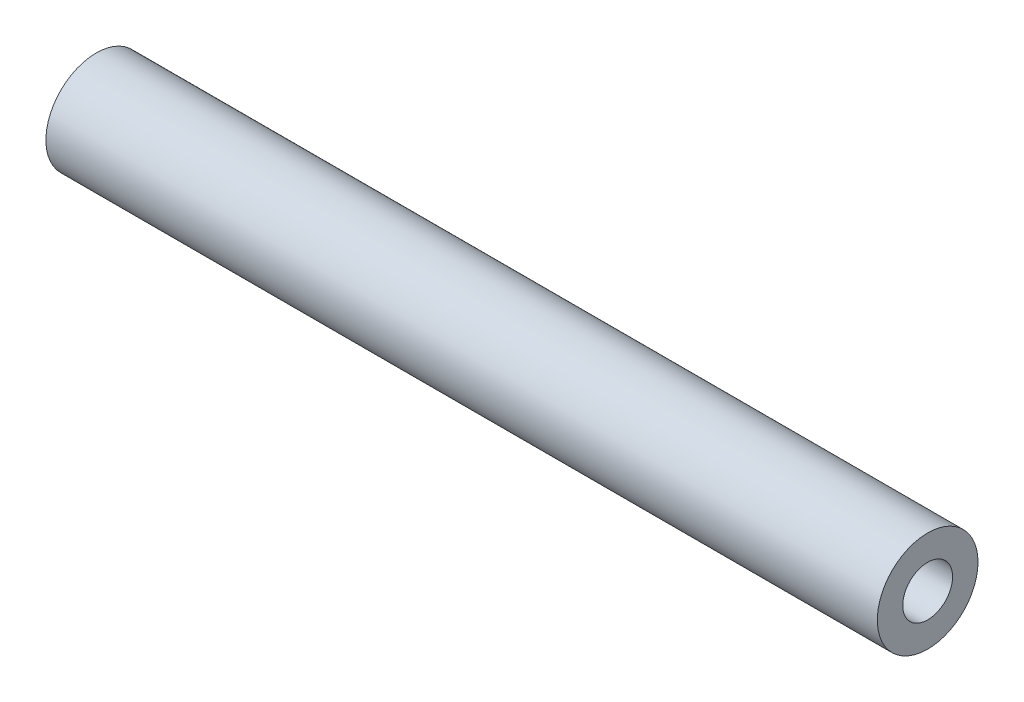
SolidWorks part; units mm, degrees
material "Natural Rubber"
ref_plane "Front Plane" through (0, 0, 0) normal (0, 0, 1) x (1, 0, 0)
ref_plane "Top Plane" through (0, 0, 0) normal (0, 1, 0) x (1, 0, 0)
ref_plane "Right Plane" through (0, 0, 0) normal (1, 0, 0) x (0, 0, -1)
sketch "Sketch2" plane through (0, 0, 0) normal (1, 0, 0) x (0, 0, -1)
  circle A0 centre (-3.3975, -0.6473) radius 15
  circle A1 centre (-3.3975, -0.6473) radius 30.275
  dimension "Inner_port_radius" = 30
  dimension "outer_radius" = 60.55
extrude "Boss-Extrude1" add sketch "Sketch2" along normal blind 500
equation "\"Inner port radius\"= \"Inner_port_radius@Sketch2\""
equation "\"Grain length\"= \"Grain_length@Boss-Extrude1\""
equation "\"outer_radius@Sketch2\"=60.55"
